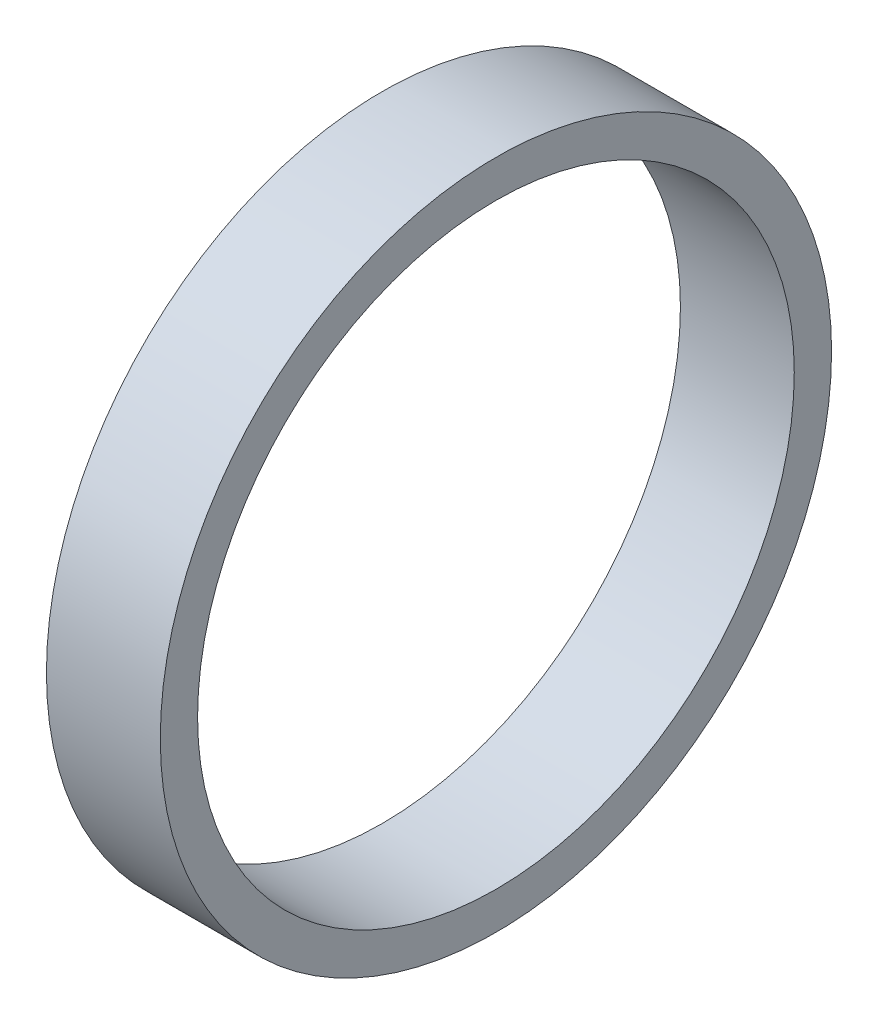
SolidWorks part; units mm, degrees
material "4140 H/T"
ref_plane "Front Plane" through (0, 0, 0) normal (0, 0, 1) x (1, 0, 0)
ref_plane "Top Plane" through (0, 0, 0) normal (0, 1, 0) x (1, 0, 0)
ref_plane "Right Plane" through (0, 0, 0) normal (1, 0, 0) x (0, 0, -1)
sketch "Sketch1" plane through (0, 0, 0) normal (1, 0, 0) x (0, 0, -1)
  circle A0 centre (0, 0) radius 33.75
  circle A1 centre (0, 0) radius 30
  dimension "D1" = 67.5
  dimension "D2" = 60
extrude "Extrude1" add sketch "Sketch1" along normal mid plane 11.45
